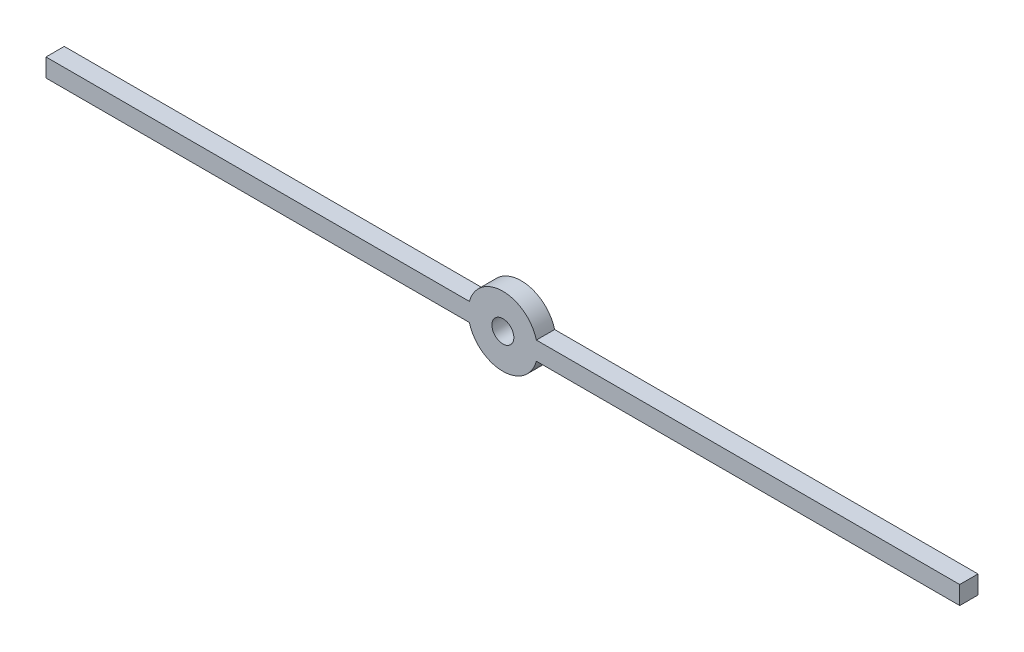
SolidWorks part; units mm, degrees
ref_plane "Front Plane" through (0, 0, 0) normal (0, 0, 1) x (1, 0, 0)
ref_plane "Top Plane" through (0, 0, 0) normal (0, 1, 0) x (1, 0, 0)
ref_plane "Right Plane" through (0, 0, 0) normal (1, 0, 0) x (0, 0, -1)
sketch "Sketch1" plane through (0, 0, 0) normal (0, 0, 1) x (1, 0, 0)
  line L0 (-2.9994, -0.06) -> (2.9994, 0.06) construction
  line L1 (-125, -2.5) -> (-9.1652, -2.5)
  line L2 (-125, -2.5) -> (-125, 2.5)
  line L3 (-125, 2.5) -> (-9.1652, 2.5)
  line L4 (125, -2.5) -> (125, 2.5)
  line L5 (9.1652, 2.5) -> (125, 2.5)
  line L6 (9.1652, -2.5) -> (125, -2.5)
  line L7 (-2.9994, 0.06) -> (2.9994, -0.06) construction
  arc A0 (9.1652, 2.5) -> (-9.1652, 2.5) centre (0, 0) ccw
  circle A1 centre (0, 0) radius 3
  arc A3 (-9.1652, -2.5) -> (9.1652, -2.5) centre (0, 0) ccw
  point P0 (0, 0)
  dimension "D3" = 19
  dimension "D4" = 6
  dimension "D1" = 5
  dimension "D2" = 250
extrude "Boss-Extrude1" add sketch "Sketch1" along normal blind 5
